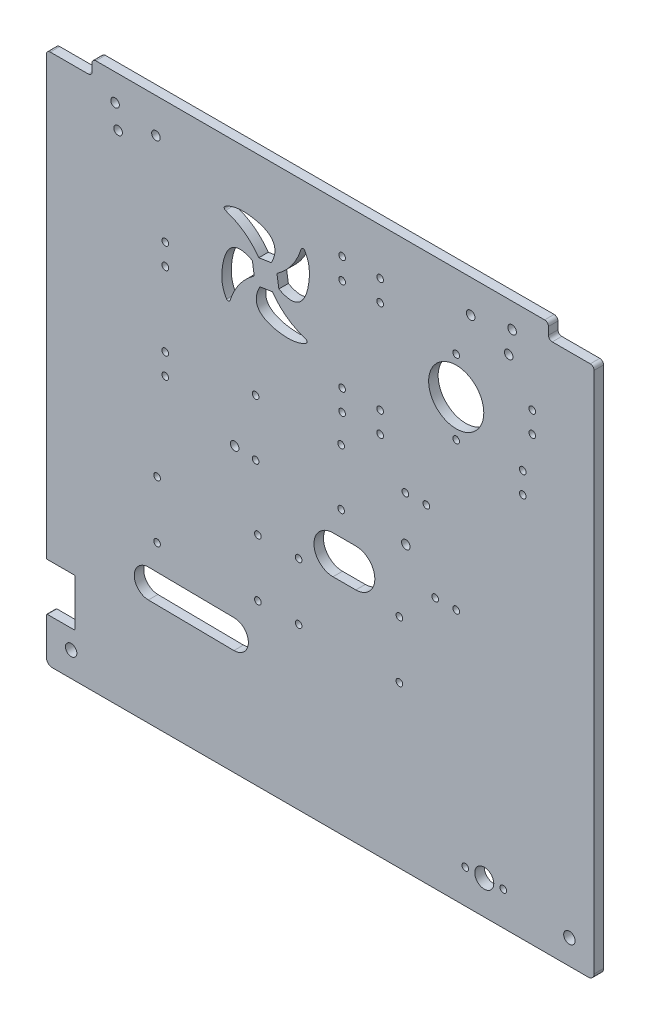
SolidWorks part; units mm, degrees
ref_plane "Front Plane" through (0, 0, 0) normal (0, 0, 1) x (1, 0, 0)
ref_plane "Top Plane" through (0, 0, 0) normal (0, 1, 0) x (1, 0, 0)
ref_plane "Right Plane" through (0, 0, 0) normal (1, 0, 0) x (0, 0, -1)
sketch "Sketch1" plane through (0, 0, 0) normal (0, 0, 1) x (1, 0, 0)
  line L0 (145, 0) -> (87.7765, 0) construction
  line L1 (0, -150) -> (0, -132.5502) construction
  line L2 (139.3564, 146) -> (143.1252, 146) construction
  line L3 (145, 1146) -> (145, 146) construction
  line L4 (141.2166, -150) -> (141.0587, -150) construction
  line L5 (-143, -147.415) -> (-143, -127) construction
  line L6 (-137.7861, 125.85) -> (-135.6228, 125.85) construction
  line L7 (122.5765, -1) -> (120.8915, -1) construction
  line L8 (119, 137.85) -> (-117, 137.85)
  line L9 (-143, 127.85) -> (-143, -101.5)
  line L10 (-140, -150) -> (142, -150)
  line L11 (145, -147) -> (145, 127.85)
  line L12 (-141, 129.85) -> (-121, 129.85)
  line L13 (1, -11.0235) -> (1, -6.5771) construction
  line L14 (-119, 131.85) -> (-119, 135.85)
  line L15 (-120, 128.3643) -> (-120, 131.3826) construction
  line L16 (-143, 145) -> (-143, 1436.2095) construction
  line L17 (122, 127.729) -> (122, 129.7643) construction
  line L18 (121, 135.85) -> (121, 131.85)
  line L19 (123, 129.85) -> (143, 129.85)
  line L20 (145, 129.85) -> (145, -893.8465) construction
  line L21 (-143, 118.9269) -> (-143, -102) construction
  line L22 (7.7013, -24.7655) -> (19.7013, -24.7655) construction
  line L23 (7.7013, -14.7655) -> (19.7013, -14.7655)
  line L24 (7.7013, -34.7655) -> (19.7013, -34.7655)
  line L25 (-138.0511, -127.0295) -> (-134.4098, -127.0295) construction
  line L26 (-142.5, -102) -> (-128.5, -102)
  line L28 (-142.5, -127) -> (-128.5, -127)
  line L29 (-128, -102.5) -> (-128, -126.5)
  line L30 (-143, -102) -> (-143, 129.85) construction
  line L31 (-143, -127.5) -> (-143, -147)
  line L32 (-143, -127) -> (-143, -1371.2253) construction
  line L33 (-89.3, -86.3889) -> (-44.3, -86.9226) construction
  line L34 (-89.2111, -78.8894) -> (-44.2111, -79.4231)
  line L35 (-89.3889, -93.8884) -> (-44.3889, -94.422)
  line L36 (78.2895, -132.25) -> (96.2105, -132.25) construction
  line L37 (-20.7654, 82.0423) -> (-21.7601, 88.6035)
  line L38 (-30.7261, 78.0731) -> (-24.165, 79.0677)
  line L39 (-34.6953, 88.0338) -> (-33.7007, 81.4726)
  line L40 (-24.7346, 92.003) -> (-31.2958, 91.0083)
  arc A0 (-143, -147) -> (-140, -150) centre (-140, -147) ccw
  arc A1 (142, -150) -> (145, -147) centre (142, -147) ccw
  circle A12 centre (132, -137) radius 3
  circle A15 centre (-130, -136.988) radius 3
  arc A22 (-121, 129.85) -> (-119, 131.85) centre (-121, 131.85) ccw
  arc A23 (-141, 129.85) -> (-143, 127.85) centre (-141, 127.85) ccw
  arc A24 (-119, 135.85) -> (-117, 137.85) centre (-117, 135.85) cw
  arc A25 (143, 129.85) -> (145, 127.85) centre (143, 127.85) cw
  arc A26 (121, 131.85) -> (123, 129.85) centre (123, 131.85) ccw
  arc A27 (121, 135.85) -> (119, 137.85) centre (119, 135.85) ccw
  circle A28 centre (80.1, 120.55) radius 2.25
  circle A29 centre (101.9, 124.85) radius 2.25
  circle A30 centre (100.1, 112.65) radius 2.25
  circle A31 centre (-85.4032, 119.6) radius 2.25
  circle A32 centre (-105.3032, 112) radius 2.25
  circle A33 centre (-106.9032, 123.8) radius 2.25
  circle A34 centre (-84.7911, -35.5) radius 1.75
  circle A35 centre (46, -0.95) radius 2.25
  circle A36 centre (-84.7911, -65.5) radius 1.75
  circle A37 centre (-44, -1.05) radius 2.25
  circle A38 centre (72.5, 79.5) radius 14.5
  circle A39 centre (-31.7911, -65.5) radius 1.75
  circle A40 centre (72.5, 60) radius 1.75
  circle A41 centre (72.5, 99) radius 1.75
  circle A42 centre (-10.3733, -65.5) radius 1.75
  circle A43 centre (42.6267, -65.5) radius 1.75
  circle A44 centre (42.6267, -35.5) radius 1.75
  circle A45 centre (-31.7911, -35.5) radius 1.75
  circle A46 centre (-10.3733, -35.5) radius 1.75
  circle A47 centre (-33, 27.5) radius 1.75
  circle A48 centre (-33, -2) radius 1.75
  circle A49 centre (12, 27.5) radius 1.75
  circle A50 centre (12, -2) radius 1.75
  circle A51 centre (12.5, 113.5) radius 1.75
  circle A52 centre (12.5, 102.46) radius 1.75
  circle A53 centre (32.5, 113.5) radius 1.75
  circle A54 centre (32.5, 102.46) radius 1.75
  circle A55 centre (12.5, 53.54) radius 1.75
  circle A56 centre (32.5, 53.54) radius 1.75
  circle A57 centre (32.5, 42.5) radius 1.77
  circle A58 centre (12.5, 42.5) radius 1.75
  circle A59 centre (45.7529, 22.5) radius 1.75
  circle A60 centre (56.7929, 22.5) radius 1.75
  circle A61 centre (61.46, -17.5) radius 1.75
  circle A62 centre (72.5, -17.5) radius 1.75
  circle A63 centre (-80.5, 23.5) radius 1.75
  circle A64 centre (-80.5, 12.46) radius 1.75
  circle A65 centre (112.5, 93.54) radius 1.75
  circle A66 centre (112.5, 82.5) radius 1.75
  circle A67 centre (107.5, 63.5) radius 1.75
  circle A68 centre (107.5, 52.46) radius 1.75
  arc A69 (7.7013, -14.7655) -> (7.7013, -34.7655) centre (7.7013, -24.7655) ccw
  arc A70 (19.7013, -34.7655) -> (19.7013, -14.7655) centre (19.7013, -24.7655) ccw
  arc A71 (-143, -127.5) -> (-142.5, -127) centre (-142.5, -127.5) cw
  arc A72 (-128.5, -127) -> (-128, -126.5) centre (-128.5, -126.5) ccw
  arc A73 (-128.5, -102) -> (-128, -102.5) centre (-128.5, -102.5) cw
  arc A74 (-142.5, -102) -> (-143, -101.5) centre (-142.5, -101.5) cw
  arc A75 (-89.2111, -78.8894) -> (-89.3889, -93.8884) centre (-89.3, -86.3889) ccw
  arc A76 (-44.3889, -94.422) -> (-44.2111, -79.4231) centre (-44.3, -86.9226) ccw
  circle A77 centre (-80.5, 73.5) radius 1.75
  circle A78 centre (-80.5, 62.46) radius 1.8
  circle A79 centre (87.25, -132.25) radius 5
  circle A80 centre (77.25, -132.25) radius 1.75
  circle A81 centre (97.25, -132.25) radius 1.75
  circle A82 centre (-27.7304, 85.038) radius 1.6828 construction
  arc A83 (-48.8189, 103.7746) -> (-49.0467, 105.5763) centre (-48.5171, 104.728) cw
  arc A84 (-8.9938, 106.1265) -> (-7.1921, 106.3543) centre (-8.0404, 105.8248) cw
  arc A85 (-6.6419, 66.3014) -> (-6.4141, 64.4998) centre (-6.9436, 65.348) cw
  arc A86 (-46.467, 63.9495) -> (-48.2686, 63.7217) centre (-47.4204, 64.2513) cw
  spline S0 degree 3 poles (-21.7601, 88.6035) (-15.5819, 92.9885) (-11.2862, 98.8837) (-8.9938, 106.1265) knots 0 0 0 0 0.918481 0.918481 0.918481 0.918481
  spline S1 degree 3 poles (-7.1921, 106.3543) (-5.9511, 104.3666) (-4.5344, 100.1657) (-4.8495, 88.0032) (-9.4886, 76.0162) (-20.7654, 82.0423) knots 0.050638 0.050638 0.050638 0.050638 0.222928 0.391636 1 1 1 1
  spline S2 degree 3 poles (-24.165, 79.0677) (-19.7799, 72.8895) (-13.8847, 68.5938) (-6.6419, 66.3014) knots 0 0 0 0 0.918481 0.918481 0.918481 0.918481
  spline S3 degree 3 poles (-6.4141, 64.4998) (-8.4018, 63.2587) (-12.6027, 61.842) (-24.7652, 62.1571) (-36.7522, 66.7962) (-30.7261, 78.0731) knots 0.050638 0.050638 0.050638 0.050638 0.222928 0.391636 1 1 1 1
  spline S4 degree 3 poles (-33.7007, 81.4726) (-39.8789, 77.0876) (-44.1746, 71.1924) (-46.467, 63.9495) knots 0 0 0 0 0.918481 0.918481 0.918481 0.918481
  spline S5 degree 3 poles (-48.2686, 63.7217) (-49.5097, 65.7095) (-50.9264, 69.9103) (-50.6113, 82.0728) (-45.9722, 94.0598) (-34.6953, 88.0338) knots 0.050638 0.050638 0.050638 0.050638 0.222928 0.391636 1 1 1 1
  spline S6 degree 3 poles (-31.2958, 91.0083) (-35.6808, 97.1865) (-41.576, 101.4822) (-48.8189, 103.7746) knots 0 0 0 0 0.918481 0.918481 0.918481 0.918481
  spline S7 degree 3 poles (-49.0467, 105.5763) (-47.0589, 106.8173) (-42.8581, 108.234) (-30.6956, 107.9189) (-18.7086, 103.2798) (-24.7346, 92.003) knots 0.050638 0.050638 0.050638 0.050638 0.222928 0.391636 1 1 1 1
  point P140 (13.7013, -24.7655)
  point P157 (-128, -127)
  point P160 (-128, -102)
  point P165 (-66.8, -86.6557)
  point P183 (87.25, -132.25)
  point P216 (-27.7304, 85.038)
  dimension "D5" = 3
  dimension "D6" = 4.5
  dimension "D7" = 4.5
  dimension "D1" = 6
  dimension "D2" = 12
  dimension "D3" = 4.5
  dimension "D4" = 6
  dimension "D8" = 29
  dimension "D9" = 3.5
  dimension "D11" = 4
  dimension "D13" = 2
  dimension "D16" = 2
  dimension "D10" = 4.5
  dimension "D17" = 4.5
  dimension "D18" = 4.5
  dimension "D19" = 4.5
  dimension "D20" = 4.5
  dimension "D21" = 3.5
  dimension "D22" = 3.5
  dimension "D23" = 3.5
  dimension "D24" = 3.5
  dimension "D25" = 3.5
  dimension "D26" = 3.5
  dimension "D27" = 3.5
  dimension "D28" = 3.5
  dimension "D29" = 3.5
  dimension "D30" = 3.5
  dimension "D31" = 3.5
  dimension "D32" = 3.5
  dimension "D33" = 3.5
  dimension "D34" = 3.5
  dimension "D35" = 3.5
  dimension "D36" = 3.5
  dimension "D37" = 3.5
  dimension "D38" = 3.5
  dimension "D39" = 3.5
  dimension "D40" = 3.54
  dimension "D41" = 3.5
  dimension "D42" = 3.5
  dimension "D43" = 3.5
  dimension "D44" = 3.5
  dimension "D45" = 3.5
  dimension "D46" = 3.5
  dimension "D47" = 3.5
  dimension "D48" = 3.5
  dimension "D49" = 3.5
  dimension "D50" = 3.5
  dimension "D51" = 3.5
  dimension "D57" = 0.5
  dimension "D60" = 3.5
  dimension "D61" = 3.6
  dimension "D62" = 10
  dimension "D63" = 3.5
  dimension "D64" = 10
  dimension "D65" = 3.5
  dimension "D66" = 10
  dimension "D67" = 4
  dimension "D68" = 1
  dimension "D12" = 1
  dimension "D14" = 4
  dimension "D15" = 1
  dimension "D52" = 20
  dimension "D53" = 12
  dimension "D54" = 15
  dimension "D55" = 25
  dimension "D56" = 23
  dimension "D58" = 15
  dimension "D59" = 45
extrude "Boss-Extrude1" add sketch "Sketch1" along normal blind 5
sketch "Sketch2" plane through (0, 0, 5) normal (0, 0, 1) x (1, 0, 0)
  circle A0 centre (1, -1) radius 33.5254 construction
